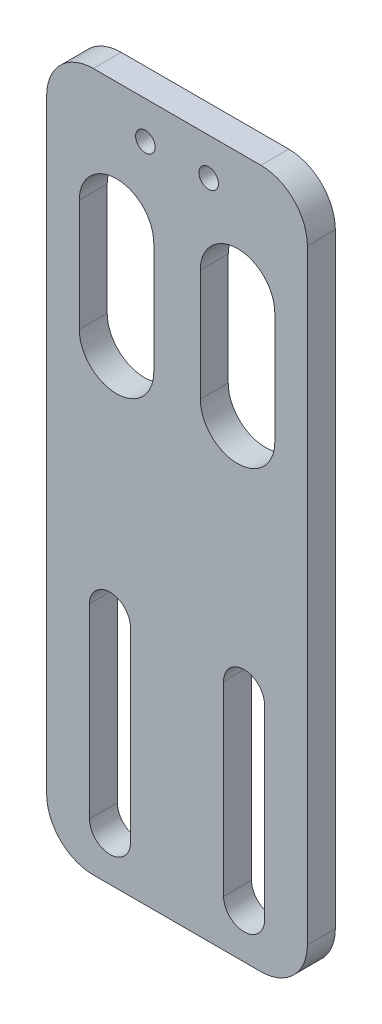
SolidWorks part; units mm, degrees
material "ABS"
ref_plane "Front Plane" through (0, 0, 0) normal (0, 0, 1) x (1, 0, 0)
ref_plane "Top Plane" through (0, 0, 0) normal (0, 1, 0) x (1, 0, 0)
ref_plane "Right Plane" through (0, 0, 0) normal (1, 0, 0) x (0, 0, -1)
sketch "Sketch1" plane through (0, 0, 0) normal (0, 0, 1) x (1, 0, 0)
  line L1 (14, 37.5) -> (-14, 37.5)
  line L2 (14, 37.5) -> (14, -37.5)
  line L3 (14, -37.5) -> (-14, -37.5)
  line L4 (-14, 37.5) -> (-14, -37.5)
  line L5 (14, 37.5) -> (-14, -37.5) construction
  line L6 (14, -37.5) -> (-14, 37.5) construction
  point P0 (0, 0)
  dimension "D1" = 28
  dimension "D2" = 75
extrude "Boss-Extrude1" add sketch "Sketch1" along normal blind 3
sketch "Sketch2" plane through (0, 0, 3) normal (0, 0, 1) x (1, 0, 0)
  line L0 (14, 37.5) -> (-14, 37.5) construction
  line L1 (-3.4, 33.5) -> (3.4, 33.5) construction
  line L2 (0, 37.5) -> (0, 33.5) construction
  line L3 (-14, 37.5) -> (-14, -37.5) construction
  line L4 (-6.5, 12.5) -> (-6.5, 24.5) construction
  line L5 (-10.5, 12.5) -> (-10.5, 24.5)
  line L6 (-2.5, 12.5) -> (-2.5, 24.5)
  line L7 (14, -37.5) -> (14, 37.5) construction
  line L8 (-14, -37.5) -> (14, -37.5) construction
  line L16 (6.5, 12.5) -> (6.5, 24.5) construction
  line L20 (2.5, 12.5) -> (2.5, 24.5)
  line L21 (10.5, 12.5) -> (10.5, 24.5)
  line L23 (-7.2, -32.5) -> (-7.2, -12.5) construction
  line L24 (-9.4, -32.5) -> (-9.4, -12.5)
  line L25 (-5, -32.5) -> (-5, -12.5)
  line L26 (7.2, -32.5) -> (7.2, -12.5) construction
  line L27 (5, -32.5) -> (5, -12.5)
  line L28 (9.4, -32.5) -> (9.4, -12.5)
  arc A0 (-9.4, -32.5) -> (-5, -32.5) centre (-7.2, -32.5) ccw
  arc A1 (-5, -12.5) -> (-9.4, -12.5) centre (-7.2, -12.5) ccw
  arc A2 (5, -32.5) -> (9.4, -32.5) centre (7.2, -32.5) ccw
  arc A3 (9.4, -12.5) -> (5, -12.5) centre (7.2, -12.5) ccw
  circle A4 centre (-3.4, 33.5) radius 1.05
  arc A5 (-10.5, 12.5) -> (-2.5, 12.5) centre (-6.5, 12.5) ccw
  circle A6 centre (3.4, 33.5) radius 1.05
  arc A7 (-2.5, 24.5) -> (-10.5, 24.5) centre (-6.5, 24.5) ccw
  arc A8 (2.5, 12.5) -> (10.5, 12.5) centre (6.5, 12.5) ccw
  arc A9 (10.5, 24.5) -> (2.5, 24.5) centre (6.5, 24.5) ccw
  point P7 (-6.5, 18.5)
  point P27 (-7.2, -22.5)
  point P57 (6.5, 18.5)
  point P63 (7.2, -22.5)
  dimension "D8" = 7.5
  dimension "D10" = 20
  dimension "D12" = 6.8
  dimension "D1" = 6.8
  dimension "D2" = 4
  dimension "D3" = 2.1
  dimension "D4" = 8
  dimension "D5" = 12
  dimension "D6" = 19
  dimension "D7" = 7.5
  dimension "D9" = 4.4
  dimension "D11" = 15
  dimension "D13" = 6.8
extrude "Cut-Extrude1" cut sketch "Sketch2" against normal through all
fillet "Fillet1" radius 5 4 edges at (-14, 37.5, 1.5) (14, 37.5, 1.5) (14, -37.5, 1.5) (-14, -37.5, 1.5)
